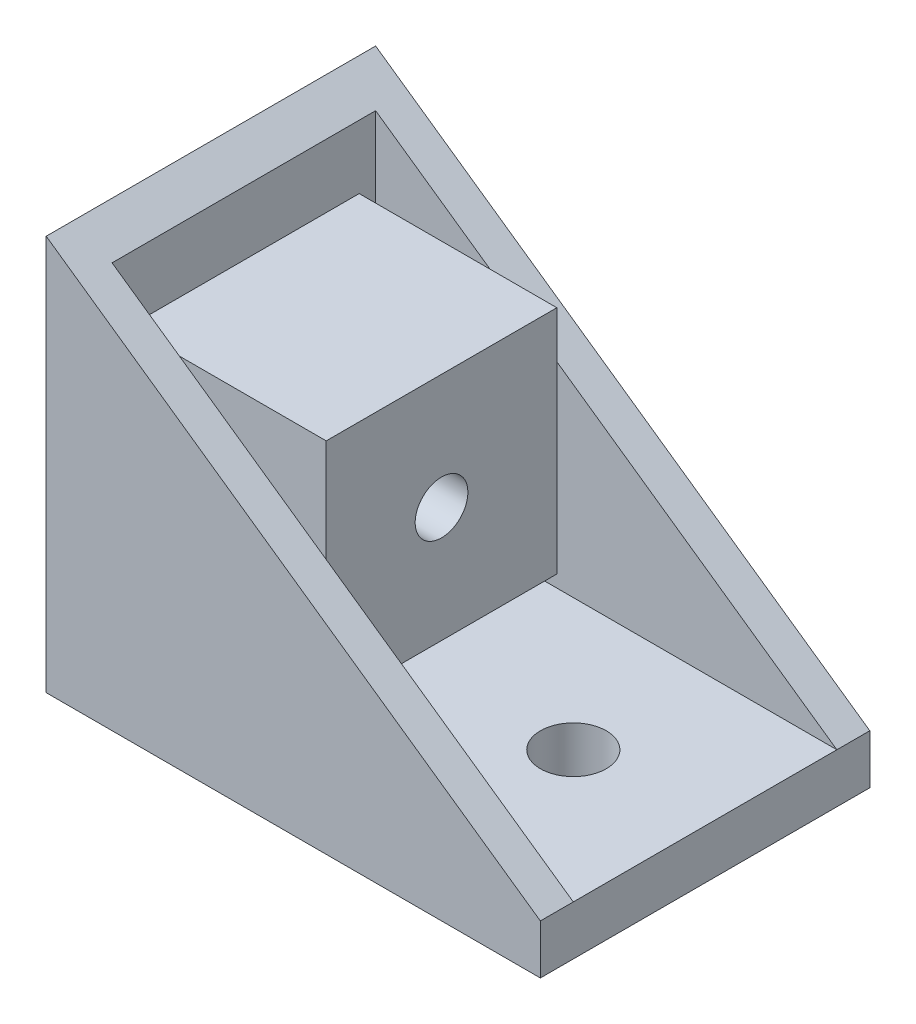
SolidWorks part; units mm, degrees
ref_plane "Alzado" through (0, 0, 0) normal (0, 0, 1) x (1, 0, 0)
ref_plane "Planta" through (0, 0, 0) normal (0, 1, 0) x (1, 0, 0)
ref_plane "Vista lateral" through (0, 0, 0) normal (1, 0, 0) x (0, 0, -1)
sketch "Croquis1" plane through (0, 0, 0) normal (0, 1, 0) x (1, 0, 0)
  line L1 (-15, -10) -> (15, -10)
  line L2 (-15, -10) -> (-15, 10)
  line L3 (-15, 10) -> (15, 10)
  line L4 (15, -10) -> (15, 10)
  line L5 (-15, -10) -> (15, 10) construction
  line L6 (-15, 10) -> (15, -10) construction
  point P0 (0, 0)
  dimension "D1" = 20
  dimension "D2" = 30
extrude "Saliente-Extruir1" add sketch "Croquis1" along normal blind 24
sketch "Croquis2" plane through (0, 0, 10) normal (0, 0, 1) x (1, 0, 0)
  line L0 (15, 0) -> (15, 3)
  line L1 (15, 24) -> (15, 0) construction
  line L2 (15, 3) -> (-15, 24)
  line L3 (-15, 24) -> (15, 24)
  line L4 (15, 24) -> (15, 3)
  line M3 (15, 0) -> (15, 24)
  line M4 (15, 24) -> (-15, 24)
  dimension "D1" = 3
extrude "Cortar-Extruir1" cut sketch "Croquis2" against normal through all contours L2 M3 M4
shell "Vaciado1" thickness 2
sketch "Croquis5" plane through (15, 0, 0) normal (1, 0, 0) x (0, 0, -1)
  line L0 (-8, 4.4) -> (-8, 0) construction
  line L1 (-10, 0) -> (10, 0) construction
  line L2 (-8, 0) -> (-8, 3) construction
  line L3 (8, 4.4) -> (8, 0) construction
  line L4 (-8, 3) -> (8, 3)
  line L7 (8, 3) -> (8, 0) construction
  line L8 (8, 0) -> (-8, 0) construction
  line L9 (-8, 3) -> (-8, 10.7759)
  line L10 (-8, 22.6) -> (-8, 2) construction
  line L11 (-8, 10.7759) -> (8, 10.7759)
  line L12 (8, 4.4) -> (8, 22.6) construction
  line L13 (8, 10.7759) -> (8, 3)
  dimension "D1" = 3
extrude "Cortar-Extruir3" cut sketch "Croquis5" against normal blind 24
sketch "Croquis6" plane through (15, 0, 0) normal (1, 0, 0) x (0, 0, -1)
  line L0 (-8, 3) -> (-8, 0)
  line L1 (-10, 0) -> (10, 0) construction
  line L2 (8, 3) -> (8, 0)
  line L3 (8, 0) -> (-8, 0)
  line L4 (-8, 3) -> (8, 3)
extrude "Saliente-Extruir2" add sketch "Croquis6" against normal through all
sketch "Croquis7" plane through (-13, 0, 0) normal (1, 0, 0) x (0, 0, -1)
  line L0 (-8, 3) -> (8, 3) construction
  line L3 (-7, 4.74) -> (7, 4.74)
  line L4 (-7, 4.74) -> (-7, 18.74)
  line L5 (-7, 18.74) -> (7, 18.74)
  line L6 (7, 4.74) -> (7, 18.74)
  line L7 (-7, 4.74) -> (7, 18.74) construction
  line L8 (-7, 18.74) -> (7, 4.74) construction
  line L10 (-8, 3) -> (-8, 22.6) construction
  point P5 (0, 11.74)
  dimension "D1" = 14
  dimension "D2" = 14
  dimension "D3" = 1.74
  dimension "D4" = 1
extrude "Saliente-Extruir3" add sketch "Croquis7" along normal blind 12
sketch "Croquis8" plane through (-1, 0, 0) normal (1, 0, 0) x (0, 0, -1)
  line L0 (0, 18.74) -> (0, 4.74) construction
  line L1 (7, 18.74) -> (-7, 18.74) construction
  line L2 (-7, 4.74) -> (7, 4.74) construction
  circle A0 centre (0, 11.74) radius 1.6
  dimension "D1" = 3.2
extrude "Cortar-Extruir5" cut sketch "Croquis8" against normal through all
sketch "Croquis9" plane through (0, 0, 0) normal (0, -1, 0) x (1, 0, 0)
  line L0 (15, 0) -> (7, 0) construction
  line L1 (15, 10) -> (15, -10) construction
  circle A0 centre (7, 0) radius 2
  dimension "D2" = 4
  dimension "D1" = 8
extrude "Cortar-Extruir6" cut sketch "Croquis9" against normal blind 12
